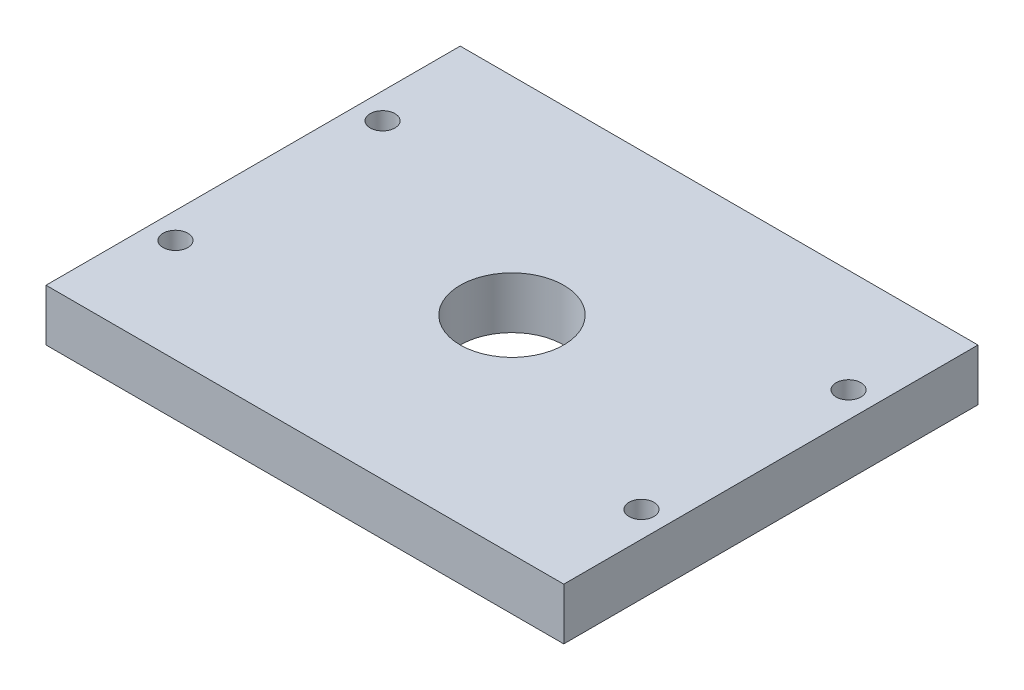
SolidWorks part; units mm, degrees
ref_plane "Front Plane" through (0, 0, 0) normal (0, 0, 1) x (1, 0, 0)
ref_plane "Top Plane" through (0, 0, 0) normal (0, 1, 0) x (1, 0, 0)
ref_plane "Right Plane" through (0, 0, 0) normal (1, 0, 0) x (0, 0, -1)
sketch "Sketch1" plane through (0, 0, 0) normal (0, 1, 0) x (1, 0, 0)
  line L1 (-25, -20) -> (25, -20)
  line L2 (-25, -20) -> (-25, 20)
  line L3 (-25, 20) -> (25, 20)
  line L4 (25, -20) -> (25, 20)
  line L5 (-25, -20) -> (25, 20) construction
  line L6 (-25, 20) -> (25, -20) construction
  circle A0 centre (0, 0) radius 5
  point P0 (0, 0)
  dimension "D1" = 50
  dimension "D2" = 40
extrude "Boss-Extrude1" add sketch "Sketch1" along normal blind 5
sketch "Sketch2" plane through (0, 0, 0) normal (0, -1, 0) x (-1, 0, 0)
  line L0 (0, -20) -> (0, 20) construction
  line L1 (25, -20) -> (-25, -20) construction
  line L2 (-25, 20) -> (25, 20) construction
  line L3 (22.5, -20) -> (22.5, 20) construction
  line L4 (25, 20) -> (25, -20) construction
  line L5 (-25, 0) -> (25, 0) construction
  line L6 (-25, -20) -> (-25, 20) construction
  point P14 (22.5, -10)
  point P15 (22.5, 10)
  point P16 (-22.5, 10)
  point P17 (-22.5, -10)
  dimension "D1" = 2.5
  dimension "D2" = 10
hole_wizard "CSK for M2 Countersunk Flat Head Screw1" positions "Sketch3" profile "Sketch4" countersink size "M2" standard "ISO" end condition through all
sketch "Sketch3" plane through (0, 0, 0) normal (0, -1, 0) x (-1, 0, 0)
  point P0 (22.5, -10)
  point P3 (22.5, 10)
  point P6 (-22.5, 10)
  point P9 (-22.5, -10)
sketch "Sketch4" plane through (-22.5, 0, 10) normal (1, 0, 0) x (0, 0, -1)
  line L0 (0, 0) -> (0, 5)
  line L1 (0, 5) -> (1.2, 5)
  line L2 (1.2, 5) -> (1.2, 1)
  line L3 (1.2, 1) -> (2.2, 0)
  line L5 (2.2, 0) -> (0, 0)
  line L6 (-1.2, 1) -> (-2.2, 0) construction
  line L11 (0, -6.35) -> (0, 107.95) construction
  dimension "Thru Hole Dia." = 2.4
  dimension "Thru Hole Depth" = 5
  dimension "Near C'Sink Dia." = 4.4
  dimension "Near C'Sink Angle" = 90
